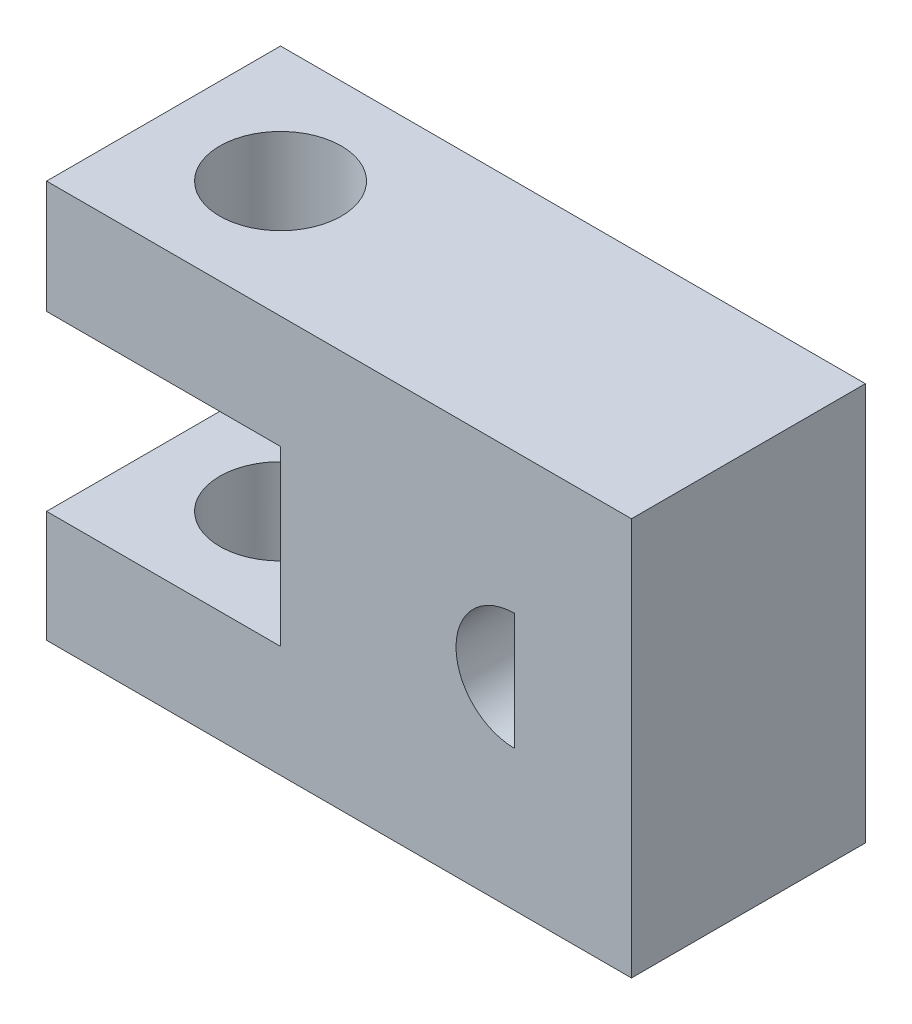
SolidWorks part; units mm, degrees
ref_plane "Front Plane" through (0, 0, 0) normal (0, 0, 1) x (1, 0, 0)
ref_plane "Top Plane" through (0, 0, 0) normal (0, 1, 0) x (1, 0, 0)
ref_plane "Right Plane" through (0, 0, 0) normal (1, 0, 0) x (0, 0, -1)
sketch "Sketch1" plane through (0, 0, 0) normal (0, 0, 1) x (1, 0, 0)
  line L1 (0, 0) -> (31.75, 0)
  line L2 (0, 0) -> (0, 21.59)
  line L3 (0, 21.59) -> (31.75, 21.59)
  line L4 (31.75, 0) -> (31.75, 21.59)
  dimension "D1" = 31.75
  dimension "D2" = 21.59
extrude "Boss-Extrude1" add sketch "Sketch1" along normal blind 12.7
sketch "Sketch2" plane through (0, 0, 12.7) normal (0, 0, 1) x (1, 0, 0)
  line L1 (0, 21.59) -> (0, 0) construction
  line L2 (0, 15.4621) -> (12.7, 15.4621)
  line L3 (12.7, 15.4621) -> (12.7, 6.0641)
  line L4 (12.7, 6.0641) -> (0, 6.0641)
  line L5 (0, 6.0641) -> (0, 15.4621)
  dimension "D1" = 12.7
  dimension "D2" = 9.398
extrude "Cut-Extrude1" cut sketch "Sketch2" against normal blind 12.954 contours L2 L3 L4 L5
sketch "Sketch3" plane through (0, 0, 0) normal (0, -1, 0) x (1, 0, 0)
  line L0 (0, 12.7) -> (0, 0) construction
  circle A0 centre (6.35, 6.35) radius 3.302
  point P3 (0, 6.35)
  dimension "D2" = 6.604
  dimension "D1" = 6.35
extrude "Cut-Extrude2" cut sketch "Sketch3" against normal blind 25.4
sketch "Sketch4" plane through (0, 0, 12.7) normal (0, 0, 1) x (1, 0, 0)
  line L0 (31.75, 10.795) -> (25.4, 10.795)
  line L1 (31.75, 0) -> (31.75, 21.59) construction
  dimension "D1" = 6.35
sketch "Sketch5" plane through (0, 0, 12.7) normal (0, 0, 1) x (1, 0, 0)
  line L1 (25.4, 13.97) -> (25.4, 7.62)
  arc A1 (25.4, 13.97) -> (25.4, 7.62) centre (25.4, 10.795) ccw
  point P4 (25.4, 10.795)
extrude "Cut-Extrude3" cut sketch "Sketch5" against normal blind 31.75
